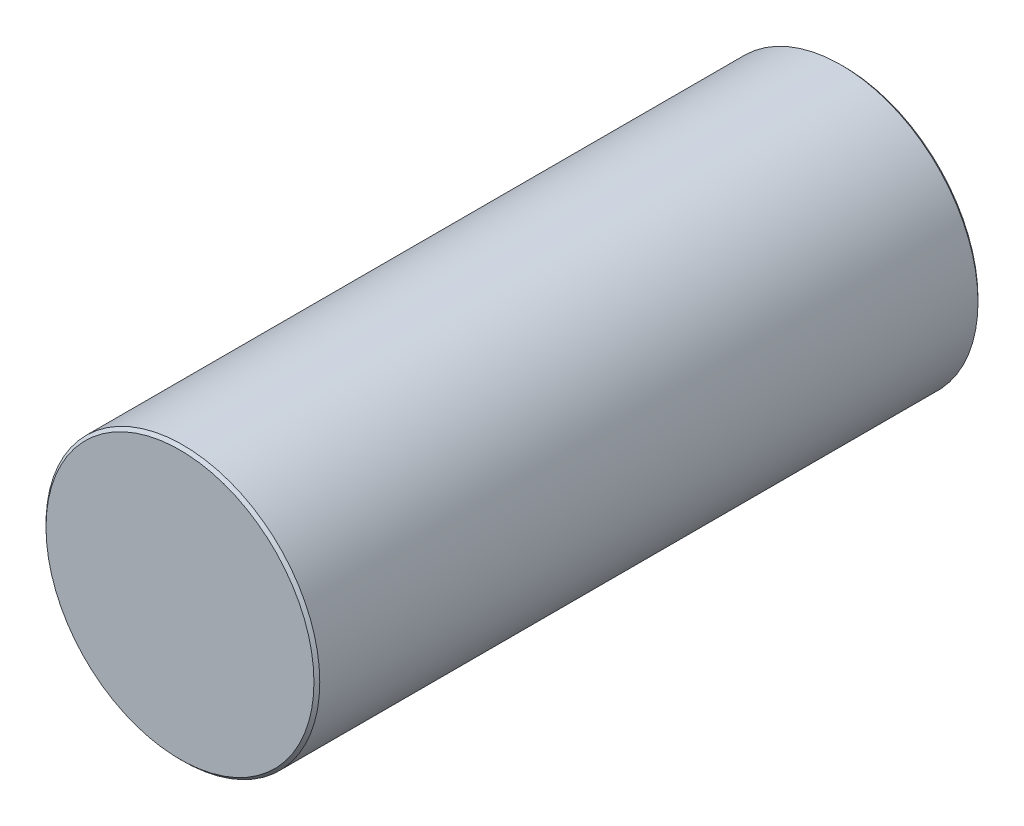
SolidWorks part; units mm, degrees
ref_plane "Front Plane" through (0, 0, 0) normal (0, 0, 1) x (1, 0, 0)
ref_plane "Top Plane" through (0, 0, 0) normal (0, 1, 0) x (1, 0, 0)
ref_plane "Right Plane" through (0, 0, 0) normal (1, 0, 0) x (0, 0, -1)
sketch "Sketch2" plane through (0, 0, 0) normal (0, 0, 1) x (1, 0, 0)
  circle A0 centre (0, 0) radius 2.35
  dimension "D1" = 4.7
extrude "Boss-Extrude1" add sketch "Sketch2" along normal blind 11.4
chamfer "Chamfer2" distance 0.05 angle 45 2 edges at (2.35, 0, 11.4) (2.35, 0, 0)
